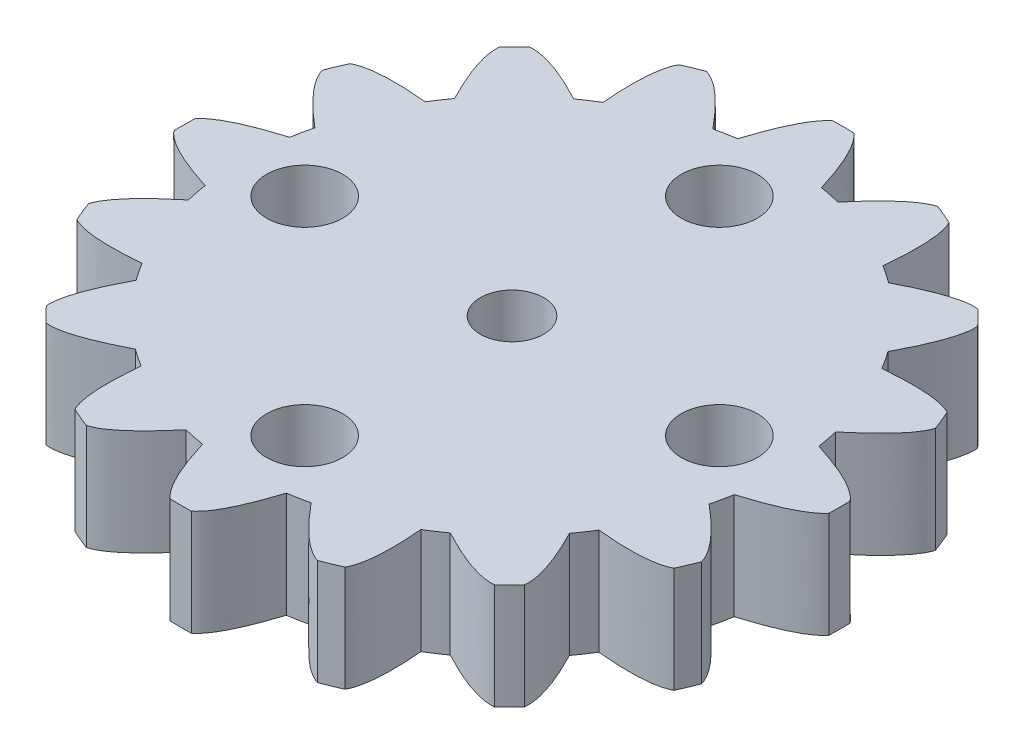
SolidWorks part; units mm, degrees
material "ABS"
ref_plane "Front Plane" through (0, 0, 0) normal (0, 0, 1) x (1, 0, 0)
ref_plane "Top Plane" through (0, 0, 0) normal (0, 1, 0) x (1, 0, 0)
ref_plane "Right Plane" through (0, 0, 0) normal (1, 0, 0) x (0, 0, -1)
sketch "Sketch1" plane through (0, 0, 0) normal (0, 1, 0) x (1, 0, 0)
  line L0 (7.543, 10.2575) -> (10.3436, 7.4246) construction
  line L2 (8.9433, 8.8411) -> (11.0767, 10.9502) construction
  line L3 (11.0767, 10.9502) -> (11.2141, 11.086)
  circle A0 centre (0, 0) radius 12.7324
  circle A1 centre (0, 0) radius 15.5756
  spline S0 degree 2 poles (10.3436, 7.4246) (13.485, 13.3309) (7.543, 10.2575) knots 0 0 0 1 1 1
  point P3 (7.543, 10.2575)
  point P4 (10.3436, 7.4246)
  point P6 (10.7195, 11.3001)
  point P12 (6.7149, 10.8177)
  point P14 (11.2141, 11.086)
  point P15 (11.4226, 10.5889)
  point P16 (5.382, 11.539)
  dimension "D1" = 25.4648
  dimension "D4" = 3
  dimension "D5" = 1
  dimension "D2" = 4
  dimension "D3" = 1
extrude "Boss-Extrude4" add sketch "Sketch1" along normal blind 5 contours A0 | A0 S0 A1
pattern_circular "CirPattern6" count 16 every 22.5 of "Boss-Extrude4"
sketch "Sketch2" plane through (0, 5, 0) normal (0, 1, 0) x (1, 0, 0)
  circle A0 centre (0, 0) radius 1.5
  circle A1 centre (9.8, 0) radius 1.8
  dimension "D1" = 3
  dimension "D2" = 3.6
extrude "Cut-Extrude1" cut sketch "Sketch2" against normal blind 10
sketch "Sketch3" plane through (0, 0, 0) normal (0, -1, 0) x (1, 0, 0)
sketch "Sketch5" plane through (0, 5, 0) normal (0, 1, 0) x (1, 0, 0)
  circle A1 centre (9.8, 0) radius 1.8
  dimension "D1" = 3.6
extrude "Cut-Extrude2" cut sketch "Sketch5" against normal blind 10
pattern_circular "CirPattern7" count 4 over 360 about axis through (0, 0, 0) along (0, 1, 0) of "Cut-Extrude2"
equation "\"number-of-teeth\"= 16"
equation "\"gear-size\"= 4mm"
equation "\"circumference\"= \"number-of-teeth\" * ( ( 1 + \"space-between-teeth\" ) * \"gear-size\" )"
equation "\"space-between-teeth\"= .25"
equation "\"D1@Sketch1\" = \"circumference\" / pi"
equation "\"D2@Sketch1\"=\"gear-size\""
equation "\"gear-length\"= 3mm"
equation "\"D4@Sketch1\"=\"gear-length\""
equation "\"D5@Sketch1\"=\"gear-size\" * \"space-between-teeth\""
equation "\"D3@Sketch1\"=\"gear-size\" * \"space-between-teeth\""
equation "\"D1@CirPattern6\"=\"number-of-teeth\""
equation "\"D2@CirPattern6\"=360 / \"number-of-teeth\""
